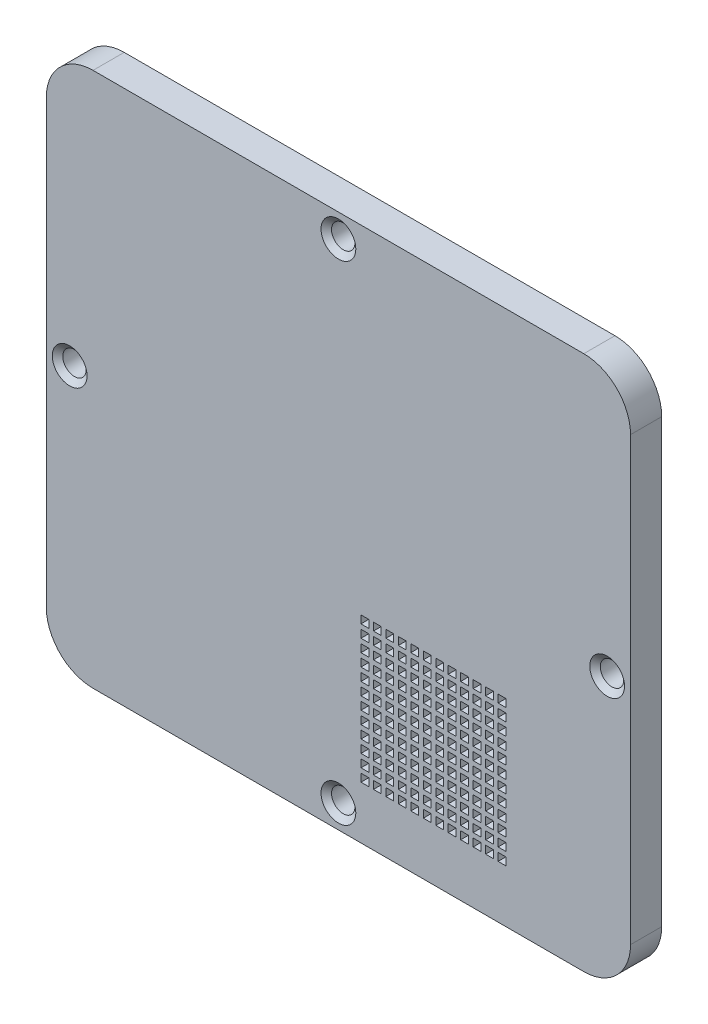
SolidWorks part; units mm, degrees
ref_plane "Front Plane" through (0, 0, 0) normal (0, 0, 1) x (1, 0, 0)
ref_plane "Top Plane" through (0, 0, 0) normal (0, 1, 0) x (1, 0, 0)
ref_plane "Right Plane" through (0, 0, 0) normal (1, 0, 0) x (0, 0, -1)
sketch "Sketch2" plane through (0, 0, 0) normal (0, 0, 1) x (1, 0, 0)
  line L8 (-6.35, 93.175) -> (-6.35, 3.175)
  line L9 (3.175, -6.35) -> (103.175, -6.35)
  line L10 (112.7, 3.175) -> (112.7, 93.175)
  line L11 (103.175, 102.7) -> (3.175, 102.7)
  arc A8 (3.175, 102.7) -> (-6.35, 93.175) centre (3.175, 93.175) ccw
  arc A9 (-6.35, 3.175) -> (3.175, -6.35) centre (3.175, 3.175) ccw
  arc A10 (103.175, -6.35) -> (112.7, 3.175) centre (103.175, 3.175) ccw
  arc A11 (112.7, 93.175) -> (103.175, 102.7) centre (103.175, 93.175) ccw
  circle A12 centre (53.175, -1.5875) radius 2.3812
  circle A13 centre (107.9375, 48.175) radius 2.3812
  circle A14 centre (53.175, 97.9375) radius 2.3812
  circle A15 centre (-1.5875, 48.175) radius 2.3813
extrude "Boss-Extrude2" add sketch "Sketch2" along normal blind 6.35
sketch "Sketch5" plane through (0, 0, 6.35) normal (0, 0, 1) x (1, 0, 0)
  line L0 (3.175, -6.35) -> (103.175, -6.35) construction
  line L1 (85.7125, 5.9675) -> (87.3, 5.9675)
  line L2 (85.7125, 5.9675) -> (85.7125, 4.38)
  line L3 (85.7125, 4.38) -> (87.3, 4.38)
  line L4 (87.3, 5.9675) -> (87.3, 4.38)
  line L5 (112.7, 3.175) -> (112.7, 93.175) construction
  line L6 (83.1725, 5.9675) -> (83.1725, 4.38)
  line L7 (83.1725, 5.9675) -> (84.76, 5.9675)
  line L8 (84.76, 5.9675) -> (84.76, 4.38)
  line L9 (83.1725, 4.38) -> (84.76, 4.38)
  line L10 (80.6325, 5.9675) -> (80.6325, 4.38)
  line L11 (80.6325, 5.9675) -> (82.22, 5.9675)
  line L12 (82.22, 5.9675) -> (82.22, 4.38)
  line L13 (80.6325, 4.38) -> (82.22, 4.38)
  line L14 (78.0925, 5.9675) -> (78.0925, 4.38)
  line L15 (78.0925, 5.9675) -> (79.68, 5.9675)
  line L16 (79.68, 5.9675) -> (79.68, 4.38)
  line L17 (78.0925, 4.38) -> (79.68, 4.38)
  line L18 (75.5525, 5.9675) -> (75.5525, 4.38)
  line L19 (75.5525, 5.9675) -> (77.14, 5.9675)
  line L20 (77.14, 5.9675) -> (77.14, 4.38)
  line L21 (75.5525, 4.38) -> (77.14, 4.38)
  line L22 (73.0125, 5.9675) -> (73.0125, 4.38)
  line L23 (73.0125, 5.9675) -> (74.6, 5.9675)
  line L24 (74.6, 5.9675) -> (74.6, 4.38)
  line L25 (73.0125, 4.38) -> (74.6, 4.38)
  line L26 (70.4725, 5.9675) -> (70.4725, 4.38)
  line L27 (70.4725, 5.9675) -> (72.06, 5.9675)
  line L28 (72.06, 5.9675) -> (72.06, 4.38)
  line L29 (70.4725, 4.38) -> (72.06, 4.38)
  line L30 (67.9325, 5.9675) -> (67.9325, 4.38)
  line L31 (67.9325, 5.9675) -> (69.52, 5.9675)
  line L32 (69.52, 5.9675) -> (69.52, 4.38)
  line L33 (67.9325, 4.38) -> (69.52, 4.38)
  line L34 (65.3925, 5.9675) -> (65.3925, 4.38)
  line L35 (65.3925, 5.9675) -> (66.98, 5.9675)
  line L36 (66.98, 5.9675) -> (66.98, 4.38)
  line L37 (65.3925, 4.38) -> (66.98, 4.38)
  line L38 (62.8525, 5.9675) -> (62.8525, 4.38)
  line L39 (62.8525, 5.9675) -> (64.44, 5.9675)
  line L40 (64.44, 5.9675) -> (64.44, 4.38)
  line L41 (62.8525, 4.38) -> (64.44, 4.38)
  line L42 (60.3125, 5.9675) -> (60.3125, 4.38)
  line L43 (60.3125, 5.9675) -> (61.9, 5.9675)
  line L44 (61.9, 5.9675) -> (61.9, 4.38)
  line L45 (60.3125, 4.38) -> (61.9, 4.38)
  line L46 (57.7725, 5.9675) -> (57.7725, 4.38)
  line L47 (57.7725, 5.9675) -> (59.36, 5.9675)
  line L48 (59.36, 5.9675) -> (59.36, 4.38)
  line L49 (57.7725, 4.38) -> (59.36, 4.38)
  line L50 (83.1725, 8.5075) -> (83.1725, 6.92)
  line L51 (83.1725, 8.5075) -> (84.76, 8.5075)
  line L52 (84.76, 8.5075) -> (84.76, 6.92)
  line L53 (83.1725, 6.92) -> (84.76, 6.92)
  line L54 (80.6325, 8.5075) -> (80.6325, 6.92)
  line L55 (80.6325, 8.5075) -> (82.22, 8.5075)
  line L56 (82.22, 8.5075) -> (82.22, 6.92)
  line L57 (80.6325, 6.92) -> (82.22, 6.92)
  line L58 (78.0925, 8.5075) -> (78.0925, 6.92)
  line L59 (78.0925, 8.5075) -> (79.68, 8.5075)
  line L60 (79.68, 8.5075) -> (79.68, 6.92)
  line L61 (78.0925, 6.92) -> (79.68, 6.92)
  line L62 (75.5525, 8.5075) -> (75.5525, 6.92)
  line L63 (75.5525, 8.5075) -> (77.14, 8.5075)
  line L64 (77.14, 8.5075) -> (77.14, 6.92)
  line L65 (75.5525, 6.92) -> (77.14, 6.92)
  line L66 (73.0125, 8.5075) -> (73.0125, 6.92)
  line L67 (73.0125, 8.5075) -> (74.6, 8.5075)
  line L68 (74.6, 8.5075) -> (74.6, 6.92)
  line L69 (73.0125, 6.92) -> (74.6, 6.92)
  line L70 (70.4725, 8.5075) -> (70.4725, 6.92)
  line L71 (70.4725, 8.5075) -> (72.06, 8.5075)
  line L72 (72.06, 8.5075) -> (72.06, 6.92)
  line L73 (70.4725, 6.92) -> (72.06, 6.92)
  line L74 (67.9325, 8.5075) -> (67.9325, 6.92)
  line L75 (67.9325, 8.5075) -> (69.52, 8.5075)
  line L76 (69.52, 8.5075) -> (69.52, 6.92)
  line L77 (67.9325, 6.92) -> (69.52, 6.92)
  line L78 (65.3925, 8.5075) -> (65.3925, 6.92)
  line L79 (65.3925, 8.5075) -> (66.98, 8.5075)
  line L80 (66.98, 8.5075) -> (66.98, 6.92)
  line L81 (65.3925, 6.92) -> (66.98, 6.92)
  line L82 (62.8525, 8.5075) -> (62.8525, 6.92)
  line L83 (62.8525, 8.5075) -> (64.44, 8.5075)
  line L84 (64.44, 8.5075) -> (64.44, 6.92)
  line L85 (62.8525, 6.92) -> (64.44, 6.92)
  line L86 (60.3125, 8.5075) -> (60.3125, 6.92)
  line L87 (60.3125, 8.5075) -> (61.9, 8.5075)
  line L88 (61.9, 8.5075) -> (61.9, 6.92)
  line L89 (60.3125, 6.92) -> (61.9, 6.92)
  line L90 (57.7725, 8.5075) -> (57.7725, 6.92)
  line L91 (57.7725, 8.5075) -> (59.36, 8.5075)
  line L92 (59.36, 8.5075) -> (59.36, 6.92)
  line L93 (57.7725, 6.92) -> (59.36, 6.92)
  line L94 (83.1725, 11.0475) -> (83.1725, 9.46)
  line L95 (83.1725, 11.0475) -> (84.76, 11.0475)
  line L96 (84.76, 11.0475) -> (84.76, 9.46)
  line L97 (83.1725, 9.46) -> (84.76, 9.46)
  line L98 (80.6325, 11.0475) -> (80.6325, 9.46)
  line L99 (80.6325, 11.0475) -> (82.22, 11.0475)
  line L100 (82.22, 11.0475) -> (82.22, 9.46)
  line L101 (80.6325, 9.46) -> (82.22, 9.46)
  line L102 (78.0925, 11.0475) -> (78.0925, 9.46)
  line L103 (78.0925, 11.0475) -> (79.68, 11.0475)
  line L104 (79.68, 11.0475) -> (79.68, 9.46)
  line L105 (78.0925, 9.46) -> (79.68, 9.46)
  line L106 (75.5525, 11.0475) -> (75.5525, 9.46)
  line L107 (75.5525, 11.0475) -> (77.14, 11.0475)
  line L108 (77.14, 11.0475) -> (77.14, 9.46)
  line L109 (75.5525, 9.46) -> (77.14, 9.46)
  line L110 (73.0125, 11.0475) -> (73.0125, 9.46)
  line L111 (73.0125, 11.0475) -> (74.6, 11.0475)
  line L112 (74.6, 11.0475) -> (74.6, 9.46)
  line L113 (73.0125, 9.46) -> (74.6, 9.46)
  line L114 (70.4725, 11.0475) -> (70.4725, 9.46)
  line L115 (70.4725, 11.0475) -> (72.06, 11.0475)
  line L116 (72.06, 11.0475) -> (72.06, 9.46)
  line L117 (70.4725, 9.46) -> (72.06, 9.46)
  line L118 (67.9325, 11.0475) -> (67.9325, 9.46)
  line L119 (67.9325, 11.0475) -> (69.52, 11.0475)
  line L120 (69.52, 11.0475) -> (69.52, 9.46)
  line L121 (67.9325, 9.46) -> (69.52, 9.46)
  line L122 (65.3925, 11.0475) -> (65.3925, 9.46)
  line L123 (65.3925, 11.0475) -> (66.98, 11.0475)
  line L124 (66.98, 11.0475) -> (66.98, 9.46)
  line L125 (65.3925, 9.46) -> (66.98, 9.46)
  line L126 (62.8525, 11.0475) -> (62.8525, 9.46)
  line L127 (62.8525, 11.0475) -> (64.44, 11.0475)
  line L128 (64.44, 11.0475) -> (64.44, 9.46)
  line L129 (62.8525, 9.46) -> (64.44, 9.46)
  line L130 (60.3125, 11.0475) -> (60.3125, 9.46)
  line L131 (60.3125, 11.0475) -> (61.9, 11.0475)
  line L132 (61.9, 11.0475) -> (61.9, 9.46)
  line L133 (60.3125, 9.46) -> (61.9, 9.46)
  line L134 (57.7725, 11.0475) -> (57.7725, 9.46)
  line L135 (57.7725, 11.0475) -> (59.36, 11.0475)
  line L136 (59.36, 11.0475) -> (59.36, 9.46)
  line L137 (57.7725, 9.46) -> (59.36, 9.46)
  line L138 (83.1725, 13.5875) -> (83.1725, 12)
  line L139 (83.1725, 13.5875) -> (84.76, 13.5875)
  line L140 (84.76, 13.5875) -> (84.76, 12)
  line L141 (83.1725, 12) -> (84.76, 12)
  line L142 (80.6325, 13.5875) -> (80.6325, 12)
  line L143 (80.6325, 13.5875) -> (82.22, 13.5875)
  line L144 (82.22, 13.5875) -> (82.22, 12)
  line L145 (80.6325, 12) -> (82.22, 12)
  line L146 (78.0925, 13.5875) -> (78.0925, 12)
  line L147 (78.0925, 13.5875) -> (79.68, 13.5875)
  line L148 (79.68, 13.5875) -> (79.68, 12)
  line L149 (78.0925, 12) -> (79.68, 12)
  line L150 (75.5525, 13.5875) -> (75.5525, 12)
  line L151 (75.5525, 13.5875) -> (77.14, 13.5875)
  line L152 (77.14, 13.5875) -> (77.14, 12)
  line L153 (75.5525, 12) -> (77.14, 12)
  line L154 (73.0125, 13.5875) -> (73.0125, 12)
  line L155 (73.0125, 13.5875) -> (74.6, 13.5875)
  line L156 (74.6, 13.5875) -> (74.6, 12)
  line L157 (73.0125, 12) -> (74.6, 12)
  line L158 (70.4725, 13.5875) -> (70.4725, 12)
  line L159 (70.4725, 13.5875) -> (72.06, 13.5875)
  line L160 (72.06, 13.5875) -> (72.06, 12)
  line L161 (70.4725, 12) -> (72.06, 12)
  line L162 (67.9325, 13.5875) -> (67.9325, 12)
  line L163 (67.9325, 13.5875) -> (69.52, 13.5875)
  line L164 (69.52, 13.5875) -> (69.52, 12)
  line L165 (67.9325, 12) -> (69.52, 12)
  line L166 (65.3925, 13.5875) -> (65.3925, 12)
  line L167 (65.3925, 13.5875) -> (66.98, 13.5875)
  line L168 (66.98, 13.5875) -> (66.98, 12)
  line L169 (65.3925, 12) -> (66.98, 12)
  line L170 (62.8525, 13.5875) -> (62.8525, 12)
  line L171 (62.8525, 13.5875) -> (64.44, 13.5875)
  line L172 (64.44, 13.5875) -> (64.44, 12)
  line L173 (62.8525, 12) -> (64.44, 12)
  line L174 (60.3125, 13.5875) -> (60.3125, 12)
  line L175 (60.3125, 13.5875) -> (61.9, 13.5875)
  line L176 (61.9, 13.5875) -> (61.9, 12)
  line L177 (60.3125, 12) -> (61.9, 12)
  line L178 (57.7725, 13.5875) -> (57.7725, 12)
  line L179 (57.7725, 13.5875) -> (59.36, 13.5875)
  line L180 (59.36, 13.5875) -> (59.36, 12)
  line L181 (57.7725, 12) -> (59.36, 12)
  line L182 (83.1725, 16.1275) -> (83.1725, 14.54)
  line L183 (83.1725, 16.1275) -> (84.76, 16.1275)
  line L184 (84.76, 16.1275) -> (84.76, 14.54)
  line L185 (83.1725, 14.54) -> (84.76, 14.54)
  line L186 (80.6325, 16.1275) -> (80.6325, 14.54)
  line L187 (80.6325, 16.1275) -> (82.22, 16.1275)
  line L188 (82.22, 16.1275) -> (82.22, 14.54)
  line L189 (80.6325, 14.54) -> (82.22, 14.54)
  line L190 (78.0925, 16.1275) -> (78.0925, 14.54)
  line L191 (78.0925, 16.1275) -> (79.68, 16.1275)
  line L192 (79.68, 16.1275) -> (79.68, 14.54)
  line L193 (78.0925, 14.54) -> (79.68, 14.54)
  line L194 (75.5525, 16.1275) -> (75.5525, 14.54)
  line L195 (75.5525, 16.1275) -> (77.14, 16.1275)
  line L196 (77.14, 16.1275) -> (77.14, 14.54)
  line L197 (75.5525, 14.54) -> (77.14, 14.54)
  line L198 (73.0125, 16.1275) -> (73.0125, 14.54)
  line L199 (73.0125, 16.1275) -> (74.6, 16.1275)
  line L200 (74.6, 16.1275) -> (74.6, 14.54)
  line L201 (73.0125, 14.54) -> (74.6, 14.54)
  line L202 (70.4725, 16.1275) -> (70.4725, 14.54)
  line L203 (70.4725, 16.1275) -> (72.06, 16.1275)
  line L204 (72.06, 16.1275) -> (72.06, 14.54)
  line L205 (70.4725, 14.54) -> (72.06, 14.54)
  line L206 (67.9325, 16.1275) -> (67.9325, 14.54)
  line L207 (67.9325, 16.1275) -> (69.52, 16.1275)
  line L208 (69.52, 16.1275) -> (69.52, 14.54)
  line L209 (67.9325, 14.54) -> (69.52, 14.54)
  line L210 (65.3925, 16.1275) -> (65.3925, 14.54)
  line L211 (65.3925, 16.1275) -> (66.98, 16.1275)
  line L212 (66.98, 16.1275) -> (66.98, 14.54)
  line L213 (65.3925, 14.54) -> (66.98, 14.54)
  line L214 (62.8525, 16.1275) -> (62.8525, 14.54)
  line L215 (62.8525, 16.1275) -> (64.44, 16.1275)
  line L216 (64.44, 16.1275) -> (64.44, 14.54)
  line L217 (62.8525, 14.54) -> (64.44, 14.54)
  line L218 (60.3125, 16.1275) -> (60.3125, 14.54)
  line L219 (60.3125, 16.1275) -> (61.9, 16.1275)
  line L220 (61.9, 16.1275) -> (61.9, 14.54)
  line L221 (60.3125, 14.54) -> (61.9, 14.54)
  line L222 (57.7725, 16.1275) -> (57.7725, 14.54)
  line L223 (57.7725, 16.1275) -> (59.36, 16.1275)
  line L224 (59.36, 16.1275) -> (59.36, 14.54)
  line L225 (57.7725, 14.54) -> (59.36, 14.54)
  line L226 (83.1725, 18.6675) -> (83.1725, 17.08)
  line L227 (83.1725, 18.6675) -> (84.76, 18.6675)
  line L228 (84.76, 18.6675) -> (84.76, 17.08)
  line L229 (83.1725, 17.08) -> (84.76, 17.08)
  line L230 (80.6325, 18.6675) -> (80.6325, 17.08)
  line L231 (80.6325, 18.6675) -> (82.22, 18.6675)
  line L232 (82.22, 18.6675) -> (82.22, 17.08)
  line L233 (80.6325, 17.08) -> (82.22, 17.08)
  line L234 (78.0925, 18.6675) -> (78.0925, 17.08)
  line L235 (78.0925, 18.6675) -> (79.68, 18.6675)
  line L236 (79.68, 18.6675) -> (79.68, 17.08)
  line L237 (78.0925, 17.08) -> (79.68, 17.08)
  line L238 (75.5525, 18.6675) -> (75.5525, 17.08)
  line L239 (75.5525, 18.6675) -> (77.14, 18.6675)
  line L240 (77.14, 18.6675) -> (77.14, 17.08)
  line L241 (75.5525, 17.08) -> (77.14, 17.08)
  line L242 (73.0125, 18.6675) -> (73.0125, 17.08)
  line L243 (73.0125, 18.6675) -> (74.6, 18.6675)
  line L244 (74.6, 18.6675) -> (74.6, 17.08)
  line L245 (73.0125, 17.08) -> (74.6, 17.08)
  line L246 (70.4725, 18.6675) -> (70.4725, 17.08)
  line L247 (70.4725, 18.6675) -> (72.06, 18.6675)
  line L248 (72.06, 18.6675) -> (72.06, 17.08)
  line L249 (70.4725, 17.08) -> (72.06, 17.08)
  line L250 (67.9325, 18.6675) -> (67.9325, 17.08)
  line L251 (67.9325, 18.6675) -> (69.52, 18.6675)
  line L252 (69.52, 18.6675) -> (69.52, 17.08)
  line L253 (67.9325, 17.08) -> (69.52, 17.08)
  line L254 (65.3925, 18.6675) -> (65.3925, 17.08)
  line L255 (65.3925, 18.6675) -> (66.98, 18.6675)
  line L256 (66.98, 18.6675) -> (66.98, 17.08)
  line L257 (65.3925, 17.08) -> (66.98, 17.08)
  line L258 (62.8525, 18.6675) -> (62.8525, 17.08)
  line L259 (62.8525, 18.6675) -> (64.44, 18.6675)
  line L260 (64.44, 18.6675) -> (64.44, 17.08)
  line L261 (62.8525, 17.08) -> (64.44, 17.08)
  line L262 (60.3125, 18.6675) -> (60.3125, 17.08)
  line L263 (60.3125, 18.6675) -> (61.9, 18.6675)
  line L264 (61.9, 18.6675) -> (61.9, 17.08)
  line L265 (60.3125, 17.08) -> (61.9, 17.08)
  line L266 (57.7725, 18.6675) -> (57.7725, 17.08)
  line L267 (57.7725, 18.6675) -> (59.36, 18.6675)
  line L268 (59.36, 18.6675) -> (59.36, 17.08)
  line L269 (57.7725, 17.08) -> (59.36, 17.08)
  line L270 (83.1725, 21.2075) -> (83.1725, 19.62)
  line L271 (83.1725, 21.2075) -> (84.76, 21.2075)
  line L272 (84.76, 21.2075) -> (84.76, 19.62)
  line L273 (83.1725, 19.62) -> (84.76, 19.62)
  line L274 (80.6325, 21.2075) -> (80.6325, 19.62)
  line L275 (80.6325, 21.2075) -> (82.22, 21.2075)
  line L276 (82.22, 21.2075) -> (82.22, 19.62)
  line L277 (80.6325, 19.62) -> (82.22, 19.62)
  line L278 (78.0925, 21.2075) -> (78.0925, 19.62)
  line L279 (78.0925, 21.2075) -> (79.68, 21.2075)
  line L280 (79.68, 21.2075) -> (79.68, 19.62)
  line L281 (78.0925, 19.62) -> (79.68, 19.62)
  line L282 (75.5525, 21.2075) -> (75.5525, 19.62)
  line L283 (75.5525, 21.2075) -> (77.14, 21.2075)
  line L284 (77.14, 21.2075) -> (77.14, 19.62)
  line L285 (75.5525, 19.62) -> (77.14, 19.62)
  line L286 (73.0125, 21.2075) -> (73.0125, 19.62)
  line L287 (73.0125, 21.2075) -> (74.6, 21.2075)
  line L288 (74.6, 21.2075) -> (74.6, 19.62)
  line L289 (73.0125, 19.62) -> (74.6, 19.62)
  line L290 (70.4725, 21.2075) -> (70.4725, 19.62)
  line L291 (70.4725, 21.2075) -> (72.06, 21.2075)
  line L292 (72.06, 21.2075) -> (72.06, 19.62)
  line L293 (70.4725, 19.62) -> (72.06, 19.62)
  line L294 (67.9325, 21.2075) -> (67.9325, 19.62)
  line L295 (67.9325, 21.2075) -> (69.52, 21.2075)
  line L296 (69.52, 21.2075) -> (69.52, 19.62)
  line L297 (67.9325, 19.62) -> (69.52, 19.62)
  line L298 (65.3925, 21.2075) -> (65.3925, 19.62)
  line L299 (65.3925, 21.2075) -> (66.98, 21.2075)
  line L300 (66.98, 21.2075) -> (66.98, 19.62)
  line L301 (65.3925, 19.62) -> (66.98, 19.62)
  line L302 (62.8525, 21.2075) -> (62.8525, 19.62)
  line L303 (62.8525, 21.2075) -> (64.44, 21.2075)
  line L304 (64.44, 21.2075) -> (64.44, 19.62)
  line L305 (62.8525, 19.62) -> (64.44, 19.62)
  line L306 (60.3125, 21.2075) -> (60.3125, 19.62)
  line L307 (60.3125, 21.2075) -> (61.9, 21.2075)
  line L308 (61.9, 21.2075) -> (61.9, 19.62)
  line L309 (60.3125, 19.62) -> (61.9, 19.62)
  line L310 (57.7725, 21.2075) -> (57.7725, 19.62)
  line L311 (57.7725, 21.2075) -> (59.36, 21.2075)
  line L312 (59.36, 21.2075) -> (59.36, 19.62)
  line L313 (57.7725, 19.62) -> (59.36, 19.62)
  line L314 (83.1725, 23.7475) -> (83.1725, 22.16)
  line L315 (83.1725, 23.7475) -> (84.76, 23.7475)
  line L316 (84.76, 23.7475) -> (84.76, 22.16)
  line L317 (83.1725, 22.16) -> (84.76, 22.16)
  line L318 (80.6325, 23.7475) -> (80.6325, 22.16)
  line L319 (80.6325, 23.7475) -> (82.22, 23.7475)
  line L320 (82.22, 23.7475) -> (82.22, 22.16)
  line L321 (80.6325, 22.16) -> (82.22, 22.16)
  line L322 (78.0925, 23.7475) -> (78.0925, 22.16)
  line L323 (78.0925, 23.7475) -> (79.68, 23.7475)
  line L324 (79.68, 23.7475) -> (79.68, 22.16)
  line L325 (78.0925, 22.16) -> (79.68, 22.16)
  line L326 (75.5525, 23.7475) -> (75.5525, 22.16)
  line L327 (75.5525, 23.7475) -> (77.14, 23.7475)
  line L328 (77.14, 23.7475) -> (77.14, 22.16)
  line L329 (75.5525, 22.16) -> (77.14, 22.16)
  line L330 (73.0125, 23.7475) -> (73.0125, 22.16)
  line L331 (73.0125, 23.7475) -> (74.6, 23.7475)
  line L332 (74.6, 23.7475) -> (74.6, 22.16)
  line L333 (73.0125, 22.16) -> (74.6, 22.16)
  line L334 (70.4725, 23.7475) -> (70.4725, 22.16)
  line L335 (70.4725, 23.7475) -> (72.06, 23.7475)
  line L336 (72.06, 23.7475) -> (72.06, 22.16)
  line L337 (70.4725, 22.16) -> (72.06, 22.16)
  line L338 (67.9325, 23.7475) -> (67.9325, 22.16)
  line L339 (67.9325, 23.7475) -> (69.52, 23.7475)
  line L340 (69.52, 23.7475) -> (69.52, 22.16)
  line L341 (67.9325, 22.16) -> (69.52, 22.16)
  line L342 (65.3925, 23.7475) -> (65.3925, 22.16)
  line L343 (65.3925, 23.7475) -> (66.98, 23.7475)
  line L344 (66.98, 23.7475) -> (66.98, 22.16)
  line L345 (65.3925, 22.16) -> (66.98, 22.16)
  line L346 (62.8525, 23.7475) -> (62.8525, 22.16)
  line L347 (62.8525, 23.7475) -> (64.44, 23.7475)
  line L348 (64.44, 23.7475) -> (64.44, 22.16)
  line L349 (62.8525, 22.16) -> (64.44, 22.16)
  line L350 (60.3125, 23.7475) -> (60.3125, 22.16)
  line L351 (60.3125, 23.7475) -> (61.9, 23.7475)
  line L352 (61.9, 23.7475) -> (61.9, 22.16)
  line L353 (60.3125, 22.16) -> (61.9, 22.16)
  line L354 (57.7725, 23.7475) -> (57.7725, 22.16)
  line L355 (57.7725, 23.7475) -> (59.36, 23.7475)
  line L356 (59.36, 23.7475) -> (59.36, 22.16)
  line L357 (57.7725, 22.16) -> (59.36, 22.16)
  line L358 (83.1725, 26.2875) -> (83.1725, 24.7)
  line L359 (83.1725, 26.2875) -> (84.76, 26.2875)
  line L360 (84.76, 26.2875) -> (84.76, 24.7)
  line L361 (83.1725, 24.7) -> (84.76, 24.7)
  line L362 (80.6325, 26.2875) -> (80.6325, 24.7)
  line L363 (80.6325, 26.2875) -> (82.22, 26.2875)
  line L364 (82.22, 26.2875) -> (82.22, 24.7)
  line L365 (80.6325, 24.7) -> (82.22, 24.7)
  line L366 (78.0925, 26.2875) -> (78.0925, 24.7)
  line L367 (78.0925, 26.2875) -> (79.68, 26.2875)
  line L368 (79.68, 26.2875) -> (79.68, 24.7)
  line L369 (78.0925, 24.7) -> (79.68, 24.7)
  line L370 (75.5525, 26.2875) -> (75.5525, 24.7)
  line L371 (75.5525, 26.2875) -> (77.14, 26.2875)
  line L372 (77.14, 26.2875) -> (77.14, 24.7)
  line L373 (75.5525, 24.7) -> (77.14, 24.7)
  line L374 (73.0125, 26.2875) -> (73.0125, 24.7)
  line L375 (73.0125, 26.2875) -> (74.6, 26.2875)
  line L376 (74.6, 26.2875) -> (74.6, 24.7)
  line L377 (73.0125, 24.7) -> (74.6, 24.7)
  line L378 (70.4725, 26.2875) -> (70.4725, 24.7)
  line L379 (70.4725, 26.2875) -> (72.06, 26.2875)
  line L380 (72.06, 26.2875) -> (72.06, 24.7)
  line L381 (70.4725, 24.7) -> (72.06, 24.7)
  line L382 (67.9325, 26.2875) -> (67.9325, 24.7)
  line L383 (67.9325, 26.2875) -> (69.52, 26.2875)
  line L384 (69.52, 26.2875) -> (69.52, 24.7)
  line L385 (67.9325, 24.7) -> (69.52, 24.7)
  line L386 (65.3925, 26.2875) -> (65.3925, 24.7)
  line L387 (65.3925, 26.2875) -> (66.98, 26.2875)
  line L388 (66.98, 26.2875) -> (66.98, 24.7)
  line L389 (65.3925, 24.7) -> (66.98, 24.7)
  line L390 (62.8525, 26.2875) -> (62.8525, 24.7)
  line L391 (62.8525, 26.2875) -> (64.44, 26.2875)
  line L392 (64.44, 26.2875) -> (64.44, 24.7)
  line L393 (62.8525, 24.7) -> (64.44, 24.7)
  line L394 (60.3125, 26.2875) -> (60.3125, 24.7)
  line L395 (60.3125, 26.2875) -> (61.9, 26.2875)
  line L396 (61.9, 26.2875) -> (61.9, 24.7)
  line L397 (60.3125, 24.7) -> (61.9, 24.7)
  line L398 (57.7725, 26.2875) -> (57.7725, 24.7)
  line L399 (57.7725, 26.2875) -> (59.36, 26.2875)
  line L400 (59.36, 26.2875) -> (59.36, 24.7)
  line L401 (57.7725, 24.7) -> (59.36, 24.7)
  line L402 (83.1725, 28.8275) -> (83.1725, 27.24)
  line L403 (83.1725, 28.8275) -> (84.76, 28.8275)
  line L404 (84.76, 28.8275) -> (84.76, 27.24)
  line L405 (83.1725, 27.24) -> (84.76, 27.24)
  line L406 (80.6325, 28.8275) -> (80.6325, 27.24)
  line L407 (80.6325, 28.8275) -> (82.22, 28.8275)
  line L408 (82.22, 28.8275) -> (82.22, 27.24)
  line L409 (80.6325, 27.24) -> (82.22, 27.24)
  line L410 (78.0925, 28.8275) -> (78.0925, 27.24)
  line L411 (78.0925, 28.8275) -> (79.68, 28.8275)
  line L412 (79.68, 28.8275) -> (79.68, 27.24)
  line L413 (78.0925, 27.24) -> (79.68, 27.24)
  line L414 (75.5525, 28.8275) -> (75.5525, 27.24)
  line L415 (75.5525, 28.8275) -> (77.14, 28.8275)
  line L416 (77.14, 28.8275) -> (77.14, 27.24)
  line L417 (75.5525, 27.24) -> (77.14, 27.24)
  line L418 (73.0125, 28.8275) -> (73.0125, 27.24)
  line L419 (73.0125, 28.8275) -> (74.6, 28.8275)
  line L420 (74.6, 28.8275) -> (74.6, 27.24)
  line L421 (73.0125, 27.24) -> (74.6, 27.24)
  line L422 (70.4725, 28.8275) -> (70.4725, 27.24)
  line L423 (70.4725, 28.8275) -> (72.06, 28.8275)
  line L424 (72.06, 28.8275) -> (72.06, 27.24)
  line L425 (70.4725, 27.24) -> (72.06, 27.24)
  line L426 (67.9325, 28.8275) -> (67.9325, 27.24)
  line L427 (67.9325, 28.8275) -> (69.52, 28.8275)
  line L428 (69.52, 28.8275) -> (69.52, 27.24)
  line L429 (67.9325, 27.24) -> (69.52, 27.24)
  line L430 (65.3925, 28.8275) -> (65.3925, 27.24)
  line L431 (65.3925, 28.8275) -> (66.98, 28.8275)
  line L432 (66.98, 28.8275) -> (66.98, 27.24)
  line L433 (65.3925, 27.24) -> (66.98, 27.24)
  line L434 (62.8525, 28.8275) -> (62.8525, 27.24)
  line L435 (62.8525, 28.8275) -> (64.44, 28.8275)
  line L436 (64.44, 28.8275) -> (64.44, 27.24)
  line L437 (62.8525, 27.24) -> (64.44, 27.24)
  line L438 (60.3125, 28.8275) -> (60.3125, 27.24)
  line L439 (60.3125, 28.8275) -> (61.9, 28.8275)
  line L440 (61.9, 28.8275) -> (61.9, 27.24)
  line L441 (60.3125, 27.24) -> (61.9, 27.24)
  line L442 (57.7725, 28.8275) -> (57.7725, 27.24)
  line L443 (57.7725, 28.8275) -> (59.36, 28.8275)
  line L444 (59.36, 28.8275) -> (59.36, 27.24)
  line L445 (57.7725, 27.24) -> (59.36, 27.24)
  line L446 (83.1725, 31.3675) -> (83.1725, 29.78)
  line L447 (83.1725, 31.3675) -> (84.76, 31.3675)
  line L448 (84.76, 31.3675) -> (84.76, 29.78)
  line L449 (83.1725, 29.78) -> (84.76, 29.78)
  line L450 (80.6325, 31.3675) -> (80.6325, 29.78)
  line L451 (80.6325, 31.3675) -> (82.22, 31.3675)
  line L452 (82.22, 31.3675) -> (82.22, 29.78)
  line L453 (80.6325, 29.78) -> (82.22, 29.78)
  line L454 (78.0925, 31.3675) -> (78.0925, 29.78)
  line L455 (78.0925, 31.3675) -> (79.68, 31.3675)
  line L456 (79.68, 31.3675) -> (79.68, 29.78)
  line L457 (78.0925, 29.78) -> (79.68, 29.78)
  line L458 (75.5525, 31.3675) -> (75.5525, 29.78)
  line L459 (75.5525, 31.3675) -> (77.14, 31.3675)
  line L460 (77.14, 31.3675) -> (77.14, 29.78)
  line L461 (75.5525, 29.78) -> (77.14, 29.78)
  line L462 (73.0125, 31.3675) -> (73.0125, 29.78)
  line L463 (73.0125, 31.3675) -> (74.6, 31.3675)
  line L464 (74.6, 31.3675) -> (74.6, 29.78)
  line L465 (73.0125, 29.78) -> (74.6, 29.78)
  line L466 (70.4725, 31.3675) -> (70.4725, 29.78)
  line L467 (70.4725, 31.3675) -> (72.06, 31.3675)
  line L468 (72.06, 31.3675) -> (72.06, 29.78)
  line L469 (70.4725, 29.78) -> (72.06, 29.78)
  line L470 (67.9325, 31.3675) -> (67.9325, 29.78)
  line L471 (67.9325, 31.3675) -> (69.52, 31.3675)
  line L472 (69.52, 31.3675) -> (69.52, 29.78)
  line L473 (67.9325, 29.78) -> (69.52, 29.78)
  line L474 (65.3925, 31.3675) -> (65.3925, 29.78)
  line L475 (65.3925, 31.3675) -> (66.98, 31.3675)
  line L476 (66.98, 31.3675) -> (66.98, 29.78)
  line L477 (65.3925, 29.78) -> (66.98, 29.78)
  line L478 (62.8525, 31.3675) -> (62.8525, 29.78)
  line L479 (62.8525, 31.3675) -> (64.44, 31.3675)
  line L480 (64.44, 31.3675) -> (64.44, 29.78)
  line L481 (62.8525, 29.78) -> (64.44, 29.78)
  line L482 (60.3125, 31.3675) -> (60.3125, 29.78)
  line L483 (60.3125, 31.3675) -> (61.9, 31.3675)
  line L484 (61.9, 31.3675) -> (61.9, 29.78)
  line L485 (60.3125, 29.78) -> (61.9, 29.78)
  line L486 (57.7725, 31.3675) -> (57.7725, 29.78)
  line L487 (57.7725, 31.3675) -> (59.36, 31.3675)
  line L488 (59.36, 31.3675) -> (59.36, 29.78)
  line L489 (57.7725, 29.78) -> (59.36, 29.78)
  line L490 (83.1725, 33.9075) -> (83.1725, 32.32)
  line L491 (83.1725, 33.9075) -> (84.76, 33.9075)
  line L492 (84.76, 33.9075) -> (84.76, 32.32)
  line L493 (83.1725, 32.32) -> (84.76, 32.32)
  line L494 (80.6325, 33.9075) -> (80.6325, 32.32)
  line L495 (80.6325, 33.9075) -> (82.22, 33.9075)
  line L496 (82.22, 33.9075) -> (82.22, 32.32)
  line L497 (80.6325, 32.32) -> (82.22, 32.32)
  line L498 (78.0925, 33.9075) -> (78.0925, 32.32)
  line L499 (78.0925, 33.9075) -> (79.68, 33.9075)
  line L500 (79.68, 33.9075) -> (79.68, 32.32)
  line L501 (78.0925, 32.32) -> (79.68, 32.32)
  line L502 (75.5525, 33.9075) -> (75.5525, 32.32)
  line L503 (75.5525, 33.9075) -> (77.14, 33.9075)
  line L504 (77.14, 33.9075) -> (77.14, 32.32)
  line L505 (75.5525, 32.32) -> (77.14, 32.32)
  line L506 (73.0125, 33.9075) -> (73.0125, 32.32)
  line L507 (73.0125, 33.9075) -> (74.6, 33.9075)
  line L508 (74.6, 33.9075) -> (74.6, 32.32)
  line L509 (73.0125, 32.32) -> (74.6, 32.32)
  line L510 (70.4725, 33.9075) -> (70.4725, 32.32)
  line L511 (70.4725, 33.9075) -> (72.06, 33.9075)
  line L512 (72.06, 33.9075) -> (72.06, 32.32)
  line L513 (70.4725, 32.32) -> (72.06, 32.32)
  line L514 (67.9325, 33.9075) -> (67.9325, 32.32)
  line L515 (67.9325, 33.9075) -> (69.52, 33.9075)
  line L516 (69.52, 33.9075) -> (69.52, 32.32)
  line L517 (67.9325, 32.32) -> (69.52, 32.32)
  line L518 (65.3925, 33.9075) -> (65.3925, 32.32)
  line L519 (65.3925, 33.9075) -> (66.98, 33.9075)
  line L520 (66.98, 33.9075) -> (66.98, 32.32)
  line L521 (65.3925, 32.32) -> (66.98, 32.32)
  line L522 (62.8525, 33.9075) -> (62.8525, 32.32)
  line L523 (62.8525, 33.9075) -> (64.44, 33.9075)
  line L524 (64.44, 33.9075) -> (64.44, 32.32)
  line L525 (62.8525, 32.32) -> (64.44, 32.32)
  line L526 (60.3125, 33.9075) -> (60.3125, 32.32)
  line L527 (60.3125, 33.9075) -> (61.9, 33.9075)
  line L528 (61.9, 33.9075) -> (61.9, 32.32)
  line L529 (60.3125, 32.32) -> (61.9, 32.32)
  line L530 (57.7725, 33.9075) -> (57.7725, 32.32)
  line L531 (57.7725, 33.9075) -> (59.36, 33.9075)
  line L532 (59.36, 33.9075) -> (59.36, 32.32)
  line L533 (57.7725, 32.32) -> (59.36, 32.32)
  line L534 (85.7125, 8.5075) -> (85.7125, 6.92)
  line L535 (85.7125, 8.5075) -> (87.3, 8.5075)
  line L536 (87.3, 8.5075) -> (87.3, 6.92)
  line L537 (85.7125, 6.92) -> (87.3, 6.92)
  line L538 (85.7125, 11.0475) -> (85.7125, 9.46)
  line L539 (85.7125, 11.0475) -> (87.3, 11.0475)
  line L540 (87.3, 11.0475) -> (87.3, 9.46)
  line L541 (85.7125, 9.46) -> (87.3, 9.46)
  line L542 (85.7125, 13.5875) -> (85.7125, 12)
  line L543 (85.7125, 13.5875) -> (87.3, 13.5875)
  line L544 (87.3, 13.5875) -> (87.3, 12)
  line L545 (85.7125, 12) -> (87.3, 12)
  line L546 (85.7125, 16.1275) -> (85.7125, 14.54)
  line L547 (85.7125, 16.1275) -> (87.3, 16.1275)
  line L548 (87.3, 16.1275) -> (87.3, 14.54)
  line L549 (85.7125, 14.54) -> (87.3, 14.54)
  line L550 (85.7125, 18.6675) -> (85.7125, 17.08)
  line L551 (85.7125, 18.6675) -> (87.3, 18.6675)
  line L552 (87.3, 18.6675) -> (87.3, 17.08)
  line L553 (85.7125, 17.08) -> (87.3, 17.08)
  line L554 (85.7125, 21.2075) -> (85.7125, 19.62)
  line L555 (85.7125, 21.2075) -> (87.3, 21.2075)
  line L556 (87.3, 21.2075) -> (87.3, 19.62)
  line L557 (85.7125, 19.62) -> (87.3, 19.62)
  line L558 (85.7125, 23.7475) -> (85.7125, 22.16)
  line L559 (85.7125, 23.7475) -> (87.3, 23.7475)
  line L560 (87.3, 23.7475) -> (87.3, 22.16)
  line L561 (85.7125, 22.16) -> (87.3, 22.16)
  line L562 (85.7125, 26.2875) -> (85.7125, 24.7)
  line L563 (85.7125, 26.2875) -> (87.3, 26.2875)
  line L564 (87.3, 26.2875) -> (87.3, 24.7)
  line L565 (85.7125, 24.7) -> (87.3, 24.7)
  line L566 (85.7125, 28.8275) -> (85.7125, 27.24)
  line L567 (85.7125, 28.8275) -> (87.3, 28.8275)
  line L568 (87.3, 28.8275) -> (87.3, 27.24)
  line L569 (85.7125, 27.24) -> (87.3, 27.24)
  line L570 (85.7125, 31.3675) -> (85.7125, 29.78)
  line L571 (85.7125, 31.3675) -> (87.3, 31.3675)
  line L572 (87.3, 31.3675) -> (87.3, 29.78)
  line L573 (85.7125, 29.78) -> (87.3, 29.78)
  line L574 (85.7125, 33.9075) -> (85.7125, 32.32)
  line L575 (85.7125, 33.9075) -> (87.3, 33.9075)
  line L576 (87.3, 33.9075) -> (87.3, 32.32)
  line L577 (85.7125, 32.32) -> (87.3, 32.32)
  dimension "D1" = 1.5875
  dimension "D2" = 1.5875
  dimension "D3" = 10.73
  dimension "D4" = 25.4
  dimension "D5" = 12
  dimension "D6" = 12
extrude "Cut-Extrude4" cut sketch "Sketch5" against normal through all
hole_wizard "CSK for #6 Flat Head Machine Screw (100)1" positions "Sketch6" profile "Sketch7" countersink size "#6" standard "ANSI Inch" end condition through all
sketch "Sketch6" plane through (0, 0, 6.35) normal (0, 0, 1) x (1, 0, 0)
  point P0 (-1.5875, 48.175)
  point P3 (53.175, 97.9375)
  point P6 (107.9375, 48.175)
  point P9 (53.175, -1.5875)
sketch "Sketch7" plane through (-1.5875, 48.175, 6.35) normal (1, 0, 0) x (0, -1, 0)
  line L0 (0, 0) -> (0, 6.35)
  line L1 (0, 6.35) -> (1.8986, 6.35)
  line L2 (1.8986, 6.35) -> (1.8986, 1.38)
  line L3 (1.8986, 1.38) -> (3.5433, 0)
  line L5 (3.5433, 0) -> (0, 0)
  line L6 (-1.8986, 1.38) -> (-3.5433, 0) construction
  line L11 (0, -6.35) -> (0, 107.95) construction
  dimension "Thru Hole Dia." = 3.7973
  dimension "Thru Hole Depth" = 6.35
  dimension "Near C'Sink Dia." = 7.0866
  dimension "Near C'Sink Angle" = 100
